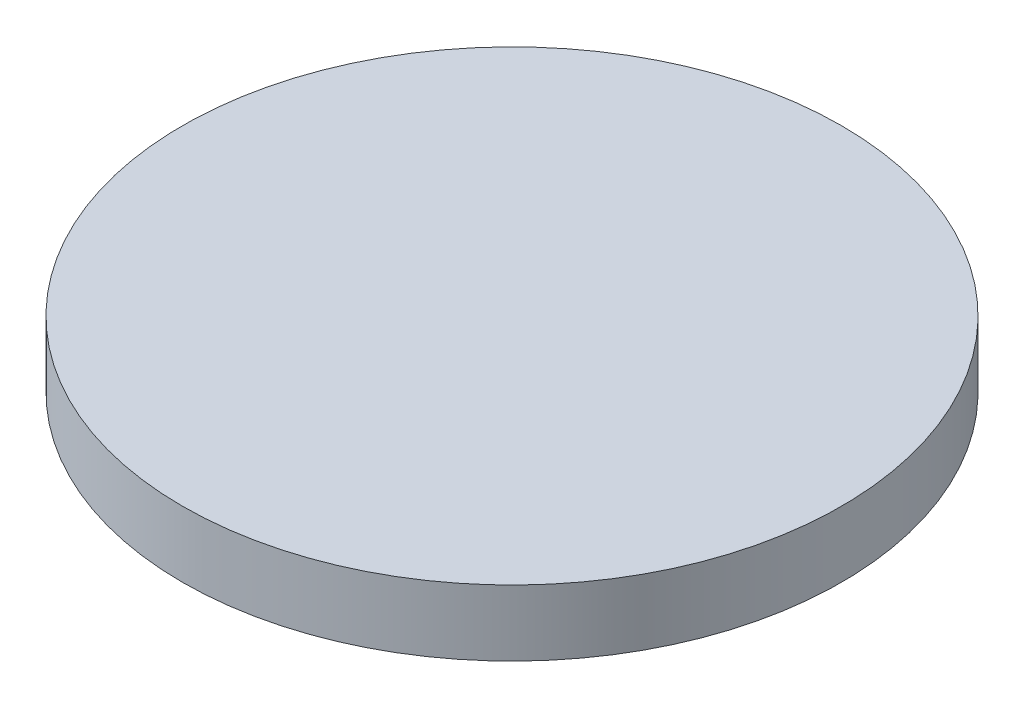
SolidWorks part; units mm, degrees
ref_plane "Front Plane" through (0, 0, 0) normal (0, 0, 1) x (1, 0, 0)
ref_plane "Top Plane" through (0, 0, 0) normal (0, 1, 0) x (1, 0, 0)
ref_plane "Right Plane" through (0, 0, 0) normal (1, 0, 0) x (0, 0, -1)
sketch "Sketch1" plane through (0, 0, 0) normal (0, 0, 1) x (1, 0, 0)
  line L1 (-31.75, 0) -> (31.75, 0) construction
  dimension "OD" = 63.5
sketch "Sketch2" plane through (0, 0, 0) normal (0, 0, 1) x (1, 0, 0)
  line L0 (0, -3.175) -> (0, 3.175)
  point P4 (0, 0)
  dimension "Thickness" = 6.35
sketch "Sketch3" plane through (0, 0, 0) normal (0, 1, 0) x (1, 0, 0)
  circle A0 centre (0, 0) radius 31.75
extrude "Boss-Extrude1" add sketch "Sketch3" along normal up to vertex (3.175 mm away) and the other way up to vertex (3.175 mm away) up to point (0, 3.175, 0) other way up to point (0, -3.175, 0)
